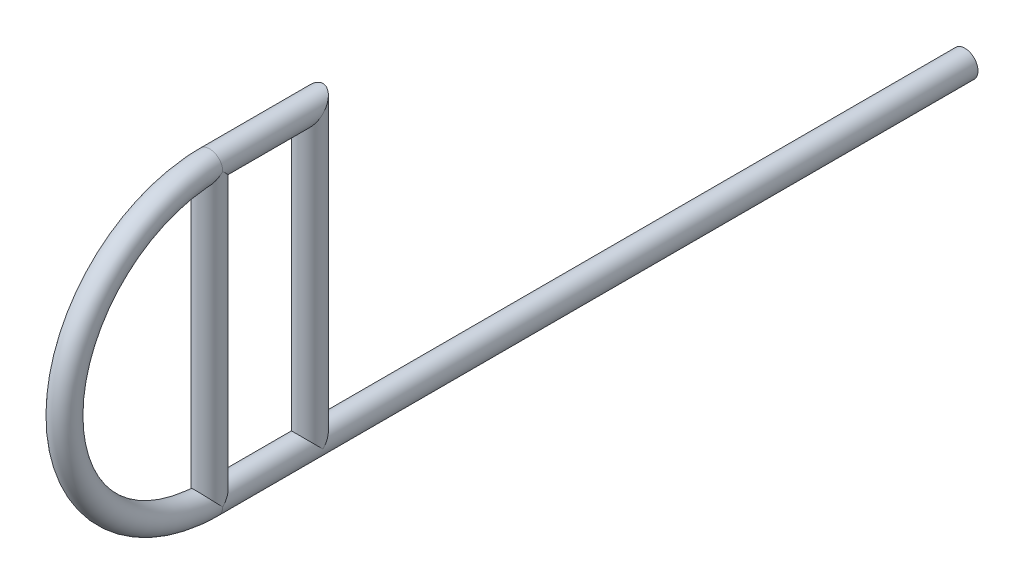
SolidWorks part; units mm, degrees
material "Yellow Painted Steel"
ref_plane "Front Plane" through (0, 0, 0) normal (1, 0, 0) x (0, 1, 0)
ref_plane "Top Plane" through (0, 0, 0) normal (0, 0, 1) x (0, 1, 0)
ref_plane "Right Plane" through (0, 0, 0) normal (0, 1, 0) x (-1, 0, 0)
sketch "Sketch1" plane through (0, 0, 0) normal (1, 0, 0) x (0, 1, 0)
  line L0 (0, 0) -> (0, 2600)
  line L2 (1000, 2210) -> (1000, 2600)
  arc A0 (0, 2600) -> (1000, 2600) centre (500, 2600) cw
  dimension "D2" = 500
  dimension "D1" = 2600
  dimension "D3" = 390
sweep "Sweep1" add path "Sketch1" circular profile diameter 90 parameters "D3"=90
sketch "Sketch9" plane through (0, 0, 0) normal (1, 0, 0) x (0, 1, 0)
  line L0 (1045, 2210) -> (955, 2300)
  line L1 (955, 2210) -> (1045, 2210) construction
  line L2 (955, 2300) -> (955, 2210)
  line L3 (955, 2210) -> (1045, 2210)
  line L4 (955, 2600) -> (955, 2210) construction
  point P7 (1038.4791, 2100)
  dimension "D1" = 45
extrude "Cut-Extrude1" cut sketch "Sketch9" against normal through all both and the other way through all
sketch "Sketch8" plane through (0, 0, 0) normal (0, 1, 0) x (-1, 0, 0)
  line L0 (-45, 2600) -> (45, 2600) construction
  line L1 (93.0764, 2210) -> (-110.5148, 2210) construction
  circle A0 centre (0, 2600) radius 45
  circle A1 centre (0, 2255) radius 45
  circle A3 centre (0, 2255) radius 45 construction
extrude "Boss-Extrude1" add sketch "Sketch8" along normal up to surface (955 mm away)
